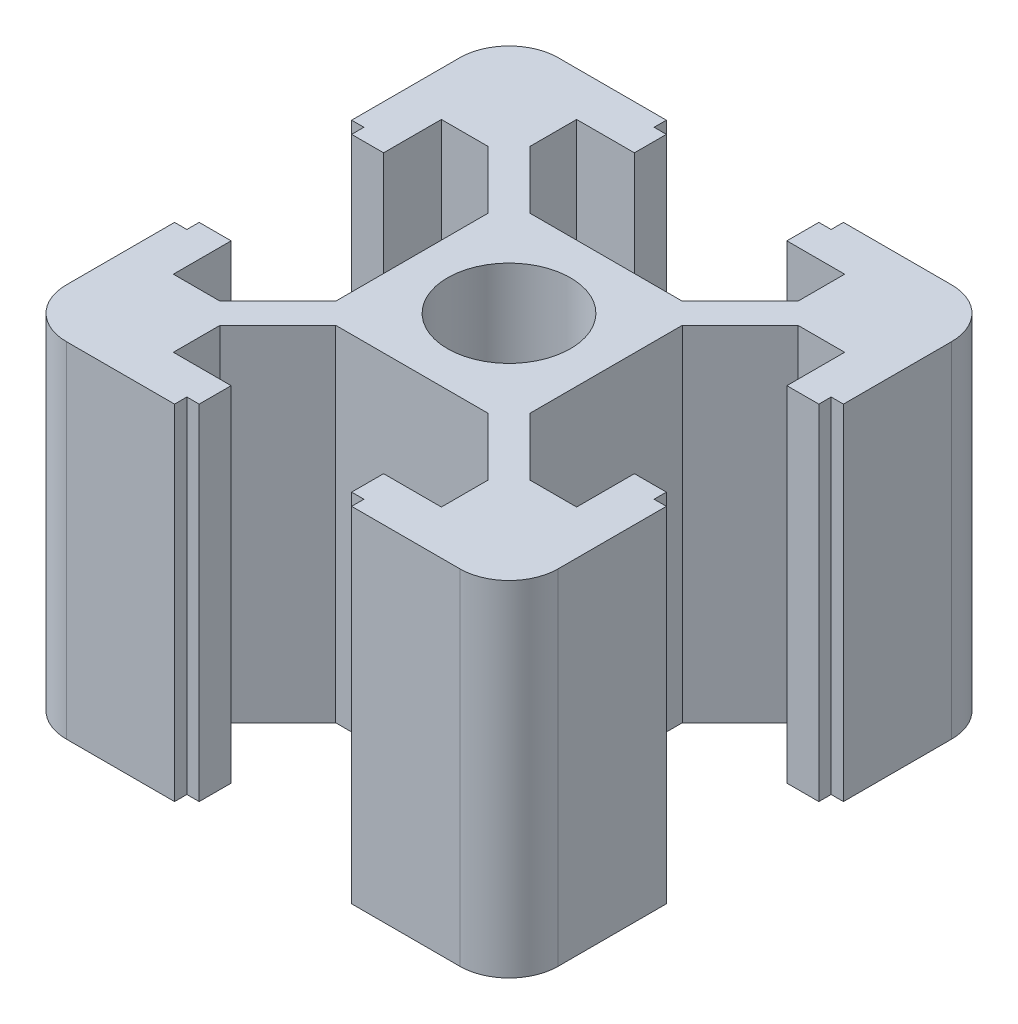
SolidWorks part; units mm, degrees
ref_plane "前视基准面" through (0, 0, 0) normal (0, 0, 1) x (1, 0, 0)
ref_plane "上视基准面" through (0, 0, 0) normal (0, 1, 0) x (1, 0, 0)
ref_plane "右视基准面" through (0, 0, 0) normal (1, 0, 0) x (0, 0, -1)
sketch "草图1" plane through (0, 0, 0) normal (0, 1, 0) x (1, 0, 0)
  line L0 (-6.2985, -5.45) -> (-3.9485, -3.1)
  line L1 (-5.45, -6.2985) -> (-3.1, -3.9485)
  line L2 (-6.2985, -5.45) -> (-8.2, -5.45)
  line L3 (-8.2, -5.45) -> (-8.2, -3.1)
  line L4 (-8.2, -3.1) -> (-10, -3.1)
  line L5 (-10, -3.1) -> (-10, -8)
  line L6 (-8, -10) -> (-3.1, -10)
  line L7 (-5.45, -6.2985) -> (-5.45, -8.2)
  line L8 (-5.45, -8.2) -> (-3.1, -8.2)
  line L9 (-3.1, -8.2) -> (-3.1, -10)
  line L10 (-3.9485, 0) -> (-3.9485, -3.1)
  line L11 (-3.1, -3.9485) -> (0, -3.9485)
  line L12 (-10, -3.6) -> (-9.5, -3.6)
  line L13 (-9.5, -3.6) -> (-9.5, -3.1)
  line L14 (-3.6, -10) -> (-3.6, -9.5)
  line L15 (-3.6, -9.5) -> (-3.1, -9.5)
  line L16 (-3.9485, 0) -> (-2.5, 0) construction
  line L17 (0, -2.5) -> (0, -3.9485) construction
  line L18 (-5.45, 6.2985) -> (-3.1, 3.9485)
  line L19 (-6.2985, 5.45) -> (-3.9485, 3.1)
  line L20 (-5.45, 6.2985) -> (-5.45, 8.2)
  line L21 (-5.45, 8.2) -> (-3.1, 8.2)
  line L22 (-3.1, 8.2) -> (-3.1, 10)
  line L23 (-3.1, 10) -> (-8, 10)
  line L24 (-10, 8) -> (-10, 3.1)
  line L25 (-6.2985, 5.45) -> (-8.2, 5.45)
  line L26 (-8.2, 5.45) -> (-8.2, 3.1)
  line L27 (-8.2, 3.1) -> (-10, 3.1)
  line L28 (-3.1, 3.9485) -> (0, 3.9485)
  line L29 (-3.9485, 3.1) -> (-3.9485, 0)
  line L30 (-3.6, 10) -> (-3.6, 9.5)
  line L31 (-3.6, 9.5) -> (-3.1, 9.5)
  line L32 (-10, 3.6) -> (-9.5, 3.6)
  line L33 (-9.5, 3.6) -> (-9.5, 3.1)
  line L34 (0, 3.9485) -> (0, 2.5) construction
  line L35 (-2.5, 0) -> (-3.9485, 0) construction
  line L36 (6.2985, 5.45) -> (3.9485, 3.1)
  line L37 (5.45, 6.2985) -> (3.1, 3.9485)
  line L38 (6.2985, 5.45) -> (8.2, 5.45)
  line L39 (8.2, 5.45) -> (8.2, 3.1)
  line L40 (8.2, 3.1) -> (10, 3.1)
  line L41 (10, 3.1) -> (10, 8)
  line L42 (8, 10) -> (3.1, 10)
  line L43 (5.45, 6.2985) -> (5.45, 8.2)
  line L44 (5.45, 8.2) -> (3.1, 8.2)
  line L45 (3.1, 8.2) -> (3.1, 10)
  line L46 (3.9485, 0) -> (3.9485, 3.1)
  line L47 (3.1, 3.9485) -> (0, 3.9485)
  line L48 (10, 3.6) -> (9.5, 3.6)
  line L49 (9.5, 3.6) -> (9.5, 3.1)
  line L50 (3.6, 10) -> (3.6, 9.5)
  line L51 (3.6, 9.5) -> (3.1, 9.5)
  line L52 (3.9485, 0) -> (2.5, 0) construction
  line L53 (0, 2.5) -> (0, 3.9485) construction
  line L54 (5.45, -6.2985) -> (3.1, -3.9485)
  line L55 (6.2985, -5.45) -> (3.9485, -3.1)
  line L56 (5.45, -6.2985) -> (5.45, -8.2)
  line L57 (5.45, -8.2) -> (3.1, -8.2)
  line L58 (3.1, -8.2) -> (3.1, -10)
  line L59 (3.1, -10) -> (8, -10)
  line L60 (10, -8) -> (10, -3.1)
  line L61 (6.2985, -5.45) -> (8.2, -5.45)
  line L62 (8.2, -5.45) -> (8.2, -3.1)
  line L63 (8.2, -3.1) -> (10, -3.1)
  line L64 (0, -3.9485) -> (3.1, -3.9485)
  line L65 (3.9485, -3.1) -> (3.9485, 0)
  line L66 (3.6, -10) -> (3.6, -9.5)
  line L67 (3.6, -9.5) -> (3.1, -9.5)
  line L68 (10, -3.6) -> (9.5, -3.6)
  line L69 (9.5, -3.6) -> (9.5, -3.1)
  line L70 (0, -3.9485) -> (0, -2.5) construction
  line L71 (2.5, 0) -> (3.9485, 0) construction
  line L72 (0, 3.9485) -> (-3.1, 3.9485) [skipped]
  circle A0 centre (0, 0) radius 2.5
  arc A1 (-10, -8) -> (-8, -10) centre (-8, -8) ccw
  arc A3 (-8, 10) -> (-10, 8) centre (-8, 8) ccw
  arc A5 (10, 8) -> (8, 10) centre (8, 8) ccw
  arc A7 (8, -10) -> (10, -8) centre (8, -8) ccw
  point P25 (-10, -10)
  point P98 (0, 0)
  dimension "D9" = 2
  dimension "D15" = 5
  dimension "D2" = 1.2
  dimension "D4" = 5.45
  dimension "D5" = 1.8
  dimension "D6" = 3.1
  dimension "D7" = 135
  dimension "D10" = 0.5
  dimension "D11" = 0.5
  dimension "D12" = 0.5
  dimension "D13" = 0.5
  dimension "D14" = 4
extrude "凸台-拉伸1" add sketch "草图1" along normal blind 14 contours L59 A7 L60 L68 L69 L63 L62 L61 L55 L65 L46 L36 L38 L39 L40 L49 L48 L41 A5 L42 L50 L51 L45 L44 L43 L37 L47 L28 L18 L20 L21 L22 L31 L30 L23 A3 L24 L32 L33 L27 L26 L25 L19 L29 L10 L0 L2 L3 L4 L13 L12
